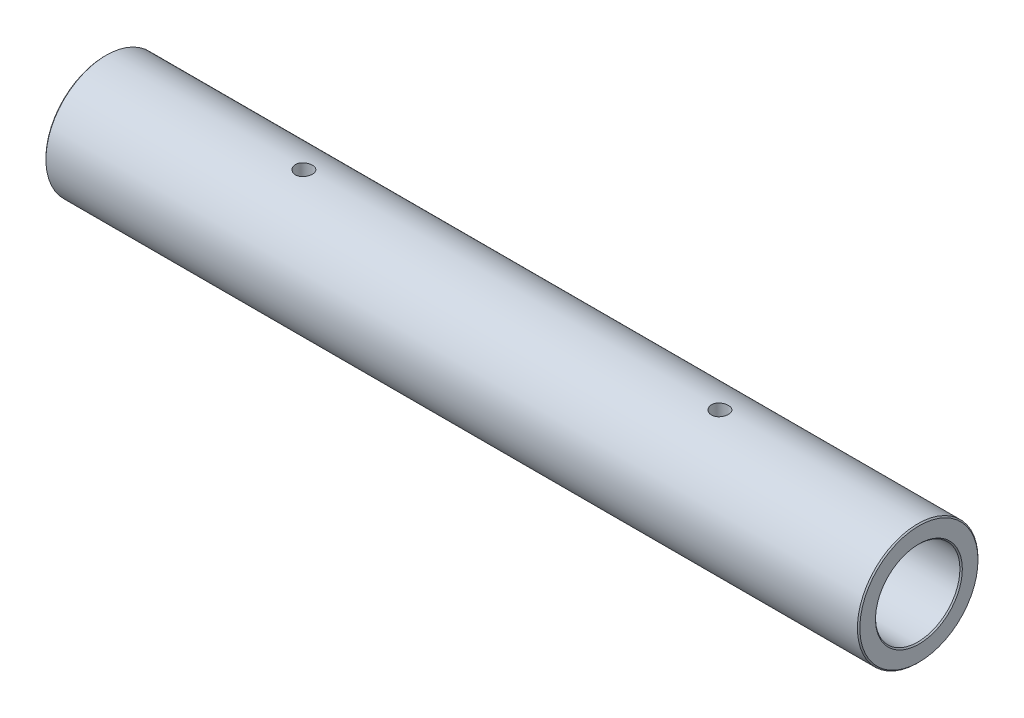
SolidWorks part; units mm, degrees
material "20"
ref_plane "前视基准面" through (0, 0, 0) normal (0, 0, 1) x (1, 0, 0)
ref_plane "上视基准面" through (0, 0, 0) normal (0, 1, 0) x (1, 0, 0)
ref_plane "右视基准面" through (0, 0, 0) normal (1, 0, 0) x (0, 0, -1)
sketch "草图1" plane through (0, 0, 0) normal (1, 0, 0) x (0, 0, -1)
  circle A0 centre (0, 0) radius 50
  circle A1 centre (0, 0) radius 35
  dimension "D1" = 100
  dimension "D2" = 70
extrude "凸台-拉伸1" add sketch "草图1" along normal mid plane 675
chamfer "倒角1" distance 1 angle 45 4 edges at (-337.5, 0, -35) (337.5, 0, -35) (337.5, 0, -50) (-337.5, 0, -50)
ref_plane "基准面1" through (0, 50, 0) normal (0, 1, 0) x (1, 0, 0)
hole_wizard "M16 螺纹孔1" positions "草图4" profile "草图5" tap size "M16" standard "GB"
sketch "草图4" plane through (0, 50, 0) normal (0, 1, 0) x (1, 0, 0)
  line L0 (0, 50) -> (0, -50) construction
  line L1 (336.5, 50) -> (-336.5, 50) construction
  line L2 (-336.5, -50) -> (336.5, -50) construction
  line L6 (336.5, 50) -> (-336.5, 50) construction
  point P0 (172.5, 0)
  point P2 (-172.5, 0)
  dimension "D1" = 345
  dimension "D2" = 50
sketch "草图5" plane through (172.5, 50, 0) normal (1, 0, 0) x (0, 0, 1)
  line L0 (0, 0) -> (0, 46.206)
  line L1 (0, 46.206) -> (7, 42)
  line L2 (7, 42) -> (7, 0)
  line L5 (7, 0) -> (0, 0)
  line L10 (0, 46.206) -> (-7, 42) construction
  line L11 (0, -6.35) -> (0, 107.95) construction
  dimension "螺纹孔钻头直径" = 14
  dimension "螺纹孔钻头深度" = 42
  dimension "导头角度" = 118
cosmetic thread "孔螺蚊线1" parameters "D1"=15.7071, "D2"=16
cosmetic thread "孔螺蚊线2" parameters "D1"=15.7071, "D2"=16
